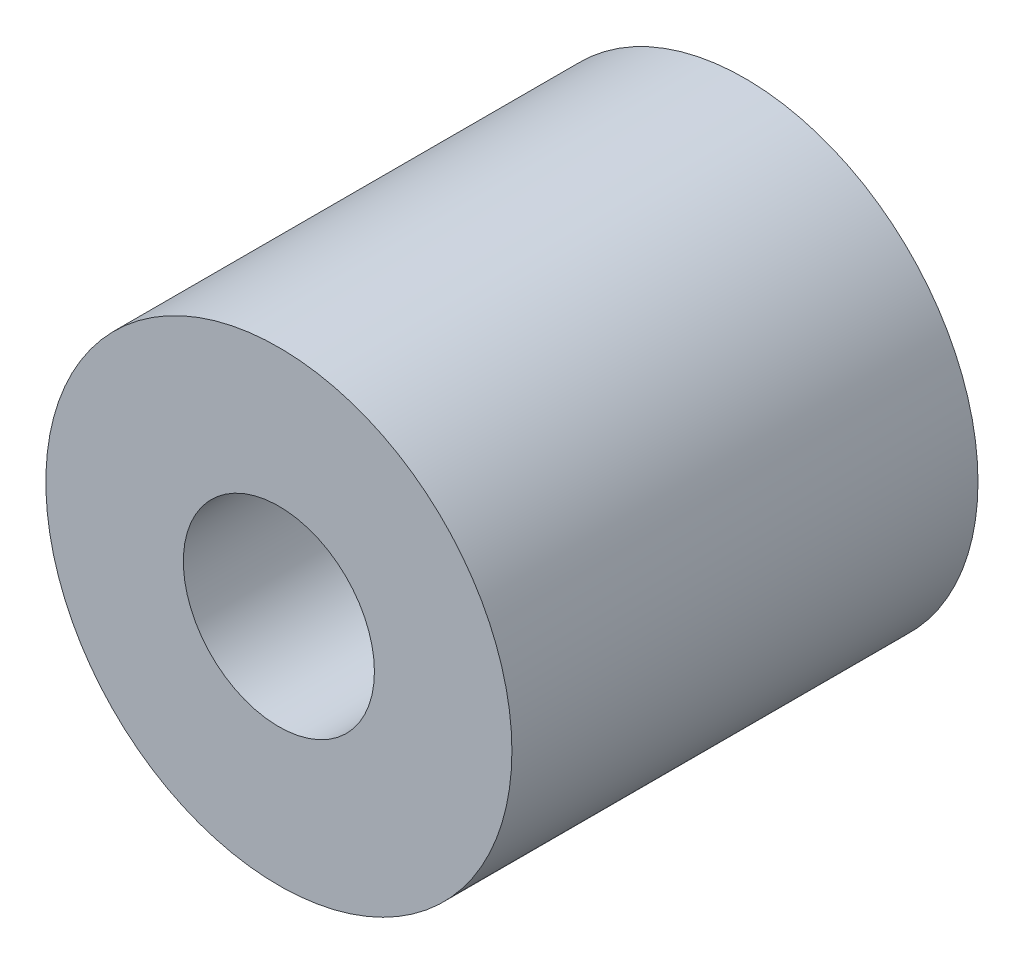
SolidWorks part; units mm, degrees
material "6061-T6 (SS)"
ref_plane "Front Plane" through (0, 0, 0) normal (0, 0, 1) x (1, 0, 0)
ref_plane "Top Plane" through (0, 0, 0) normal (0, 1, 0) x (1, 0, 0)
ref_plane "Right Plane" through (0, 0, 0) normal (1, 0, 0) x (0, 0, -1)
sketch "Sketch1" plane through (0, 0, 0) normal (0, 0, 1) x (1, 0, 0)
  circle A0 centre (0, 0) radius 2.6035
  circle A1 centre (0, 0) radius 6.35
  dimension "D1" = 5.207
  dimension "D2" = 12.7
extrude "Boss-Extrude1" add sketch "Sketch1" along normal mid plane 12.7
